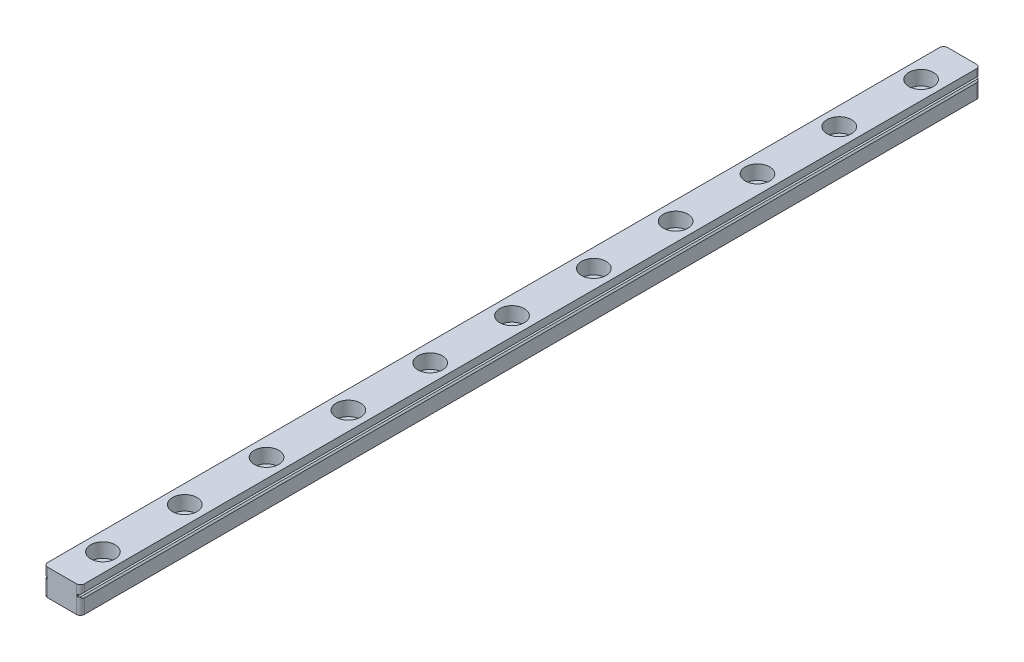
SolidWorks part; units mm, degrees
material "镀铬不锈钢"
ref_plane "前视基准面" through (0, 0, 0) normal (0, 0, 1) x (1, 0, 0)
ref_plane "上视基准面" through (0, 0, 0) normal (0, 1, 0) x (1, 0, 0)
ref_plane "右视基准面" through (0, 0, 0) normal (1, 0, 0) x (0, 0, -1)
sketch "草图1" plane through (0, 0, 0) normal (0, 0, 1) x (1, 0, 0)
  line L0 (-4.5, -3.6634) -> (4.5, -3.6634)
  line L1 (0, -3.6634) -> (0, 3.6634) construction
  line L2 (4.5, -3.6634) -> (4.5, -0.1634)
  line L3 (4.5, -0.1634) -> (4.1464, 0.1901)
  line L4 (4.1464, 0.1901) -> (3.6464, 0.1901)
  line L5 (3.6464, 0.1901) -> (3.6464, 0.6901)
  line L6 (3.6464, 0.6901) -> (4.1464, 0.6901)
  line L7 (4.1464, 0.6901) -> (4.5, 1.0437)
  line L8 (4.5, 1.0437) -> (4.5, 2.8366)
  line L9 (4.5, 2.8366) -> (-4.5, 2.8366)
  line L10 (-4.5, 1.0437) -> (-4.5, 2.8366)
  line L11 (-4.1464, 0.6901) -> (-4.5, 1.0437)
  line L12 (-3.6464, 0.6901) -> (-4.1464, 0.6901)
  line L13 (-3.6464, 0.1901) -> (-3.6464, 0.6901)
  line L14 (-4.1464, 0.1901) -> (-3.6464, 0.1901)
  line L15 (-4.5, -0.1634) -> (-4.1464, 0.1901)
  line L16 (-4.5, -3.6634) -> (-4.5, -0.1634)
  point P13 (0, 2.8366)
extrude "凸台-拉伸1" add sketch "草图1" along normal blind 220
sketch "草图2" plane through (0, 2.8366, 0) normal (0, 1, 0) x (1, 0, 0)
  line L0 (-4.5, -220) -> (-4.5, 0) construction
  line L1 (4.5, -220) -> (-4.5, -220) construction
  circle A0 centre (0, -210) radius 3
  dimension "D1" = 6
  dimension "D2" = 4.5
  dimension "D3" = 10
extrude "切除-拉伸1" cut sketch "草图2" against normal blind 3.5
sketch "草图3" plane through (0, -0.6634, 0) normal (0, 1, 0) x (1, 0, 0)
  circle A0 centre (0, -210) radius 1.75
  dimension "D1" = 3.5
extrude "切除-拉伸2" cut sketch "草图3" against normal through all
pattern_linear "阵列(线性)1" count 30 spacing 20 along (0, 0, -1) of "切除-拉伸1", "切除-拉伸2"
fillet "圆角1" radius 1 4 edges at (4.5, -1.9134, 0) (-4.5, -1.9134, 0) (4.5, -1.9134, 220) (-4.5, -1.9134, 220)
